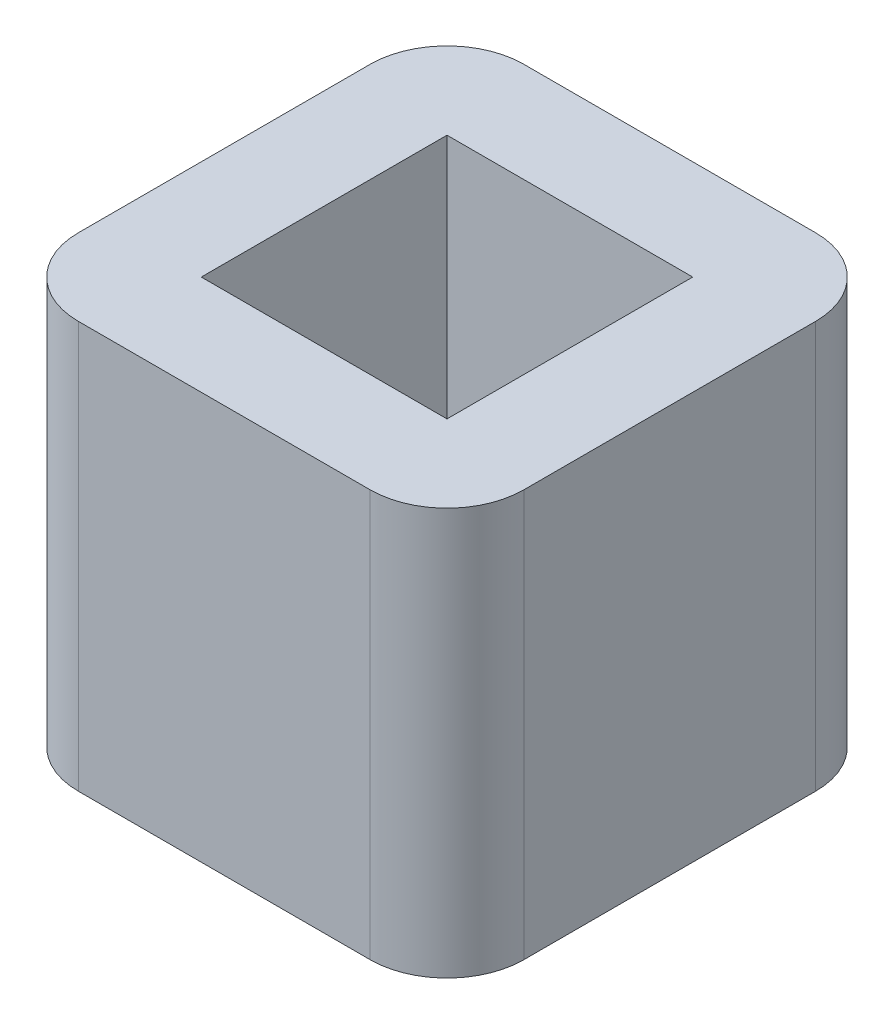
SolidWorks part; units mm, degrees
material "Copper"
ref_plane "Front Plane" through (0, 0, 0) normal (0, 0, 1) x (1, 0, 0)
ref_plane "Top Plane" through (0, 0, 0) normal (0, 1, 0) x (1, 0, 0)
ref_plane "Right Plane" through (0, 0, 0) normal (1, 0, 0) x (0, 0, -1)
sketch "Sketch2" plane through (0, 0, 0) normal (0, 1, 0) x (1, 0, 0)
  line L0 (-29, 19) -> (-29, -19)
  line L1 (-16, 16) -> (16, 16)
  line L2 (-16, 16) -> (-16, -16)
  line L3 (-16, -16) -> (16, -16)
  line L4 (16, 16) -> (16, -16)
  line L5 (-16, 16) -> (16, -16) construction
  line L6 (-16, -16) -> (16, 16) construction
  line L7 (-19, -29) -> (19, -29)
  line L8 (29, 19) -> (29, -19)
  line L9 (-19, 29) -> (19, 29)
  line L10 (29, 29) -> (29, -29) construction
  line L11 (-29, 29) -> (29, 29) construction
  line L12 (-29, -29) -> (29, -29) construction
  line L13 (-29, 29) -> (-29, -29) construction
  arc A0 (29, 19) -> (19, 29) centre (19, 19) ccw
  arc A1 (29, -19) -> (19, -29) centre (19, -19) cw
  arc A2 (-19, -29) -> (-29, -19) centre (-19, -19) cw
  arc A3 (-29, 19) -> (-19, 29) centre (-19, 19) cw
  point P0 (0, 0)
  dimension "D3" = 10
  dimension "D1" = 32
  dimension "D2" = 13
extrude "Boss-Extrude1" add sketch "Sketch2" along normal mid plane 53
